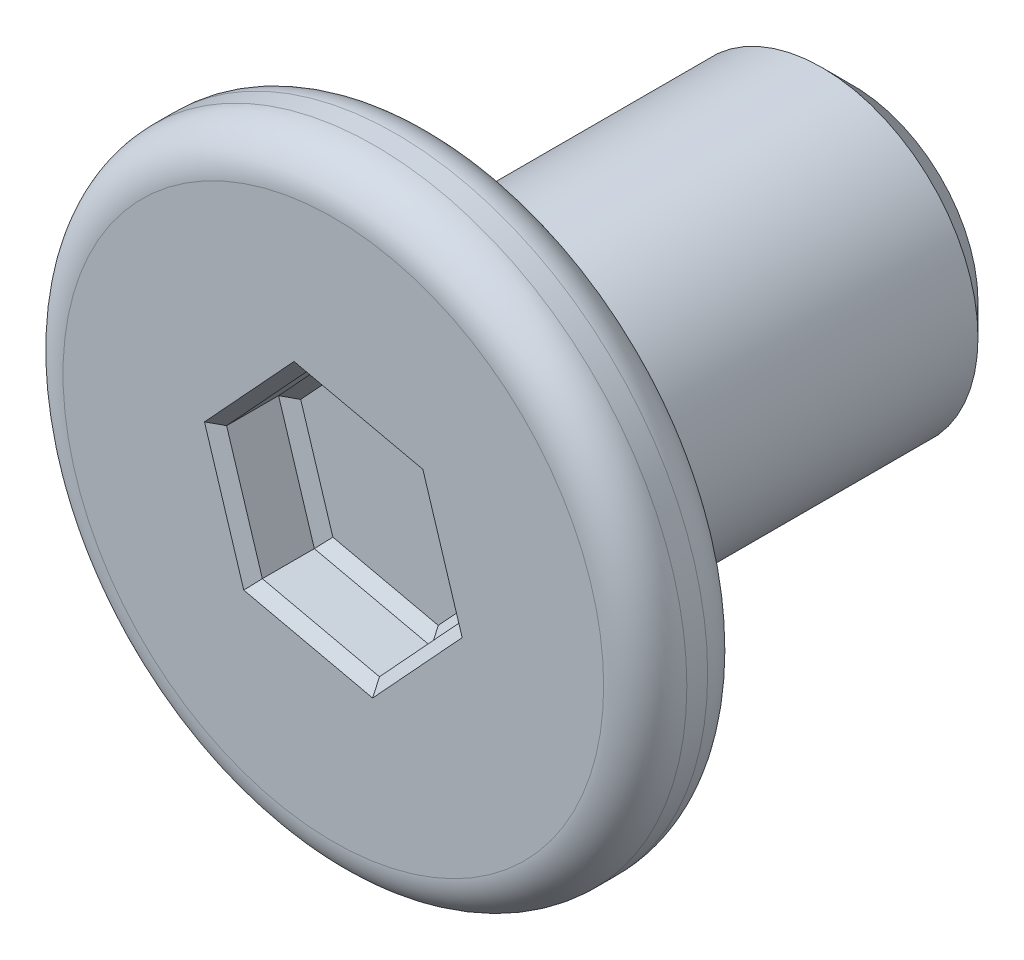
SolidWorks part; units mm, degrees
ref_plane "前视基准面" through (0, 0, 0) normal (0, 0, 1) x (1, 0, 0)
ref_plane "上视基准面" through (0, 0, 0) normal (0, 1, 0) x (1, 0, 0)
ref_plane "右视基准面" through (0, 0, 0) normal (1, 0, 0) x (0, 0, -1)
sketch "草图1" plane through (0, 0, 0) normal (0, 0, 1) x (1, 0, 0)
  circle A0 centre (0, 0) radius 3
  dimension "D1" = 6
extrude "凸台-拉伸1" add sketch "草图1" along normal blind 1
sketch "草图2" plane through (0, 0, 0) normal (0, 0, -1) x (-1, 0, 0)
  circle A0 centre (0, 0) radius 1.5
  dimension "D1" = 3
extrude "凸台-拉伸2" add sketch "草图2" along normal blind 4
fillet "圆角1" radius 0.4 2 edges at (3, 0, 1) (3, 0, 0)
sketch "草图3" plane through (0, 0, 1) normal (0, 0, 1) x (1, 0, 0)
  line L1 (0.3436, -1.1024) -> (1.1265, -0.2536)
  line L2 (1.1265, -0.2536) -> (0.7829, 0.8488)
  line L3 (0.7829, 0.8488) -> (-0.3436, 1.1024)
  line L4 (-0.3436, 1.1024) -> (-1.1265, 0.2536)
  line L5 (-1.1265, 0.2536) -> (-0.7829, -0.8488)
  line L6 (-0.7829, -0.8488) -> (0.3436, -1.1024)
  circle A0 centre (0, 0) radius 1 construction
  dimension "D1" = 2
extrude "切除-拉伸1" cut sketch "草图3" against normal blind 0.7
chamfer "倒角1" distance 0.1 angle 45 12 edges at (-0.2196, -0.9756, 0.3) (-0.9547, -0.2976, 0.3) (-0.7351, 0.678, 0.3) (0.2196, 0.9756, 0.3) (0.9547, 0.2976, 0.3) (0.7351, -0.678, 0.3) (-0.2196, -0.9756, 1) (-0.9547, -0.2976, 1) (-0.7351, 0.678, 1) (0.2196, 0.9756, 1) (0.9547, 0.2976, 1) (0.7351, -0.678, 1)
chamfer "倒角2" distance 0.3 angle 45 1 edges at (-1.5, 0, -4)
